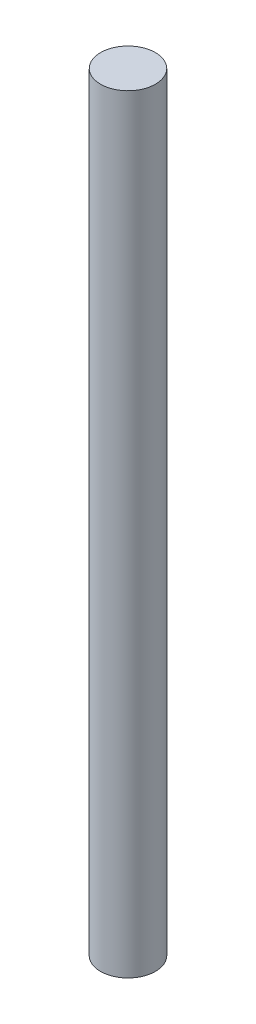
SolidWorks part; units mm, degrees
ref_plane "Plano frontal" through (0, 0, 0) normal (0, 0, 1) x (1, 0, 0)
ref_plane "Plano superior" through (0, 0, 0) normal (0, 1, 0) x (1, 0, 0)
ref_plane "Plano direito" through (0, 0, 0) normal (1, 0, 0) x (0, 0, -1)
sketch "Esboço1" plane through (0, 0, 0) normal (0, 1, 0) x (1, 0, 0)
  circle A0 centre (0, 0) radius 2.38
  dimension "D1" = 4.76
extrude "Ressalto-extrusão1" add sketch "Esboço1" along normal blind 66.689
